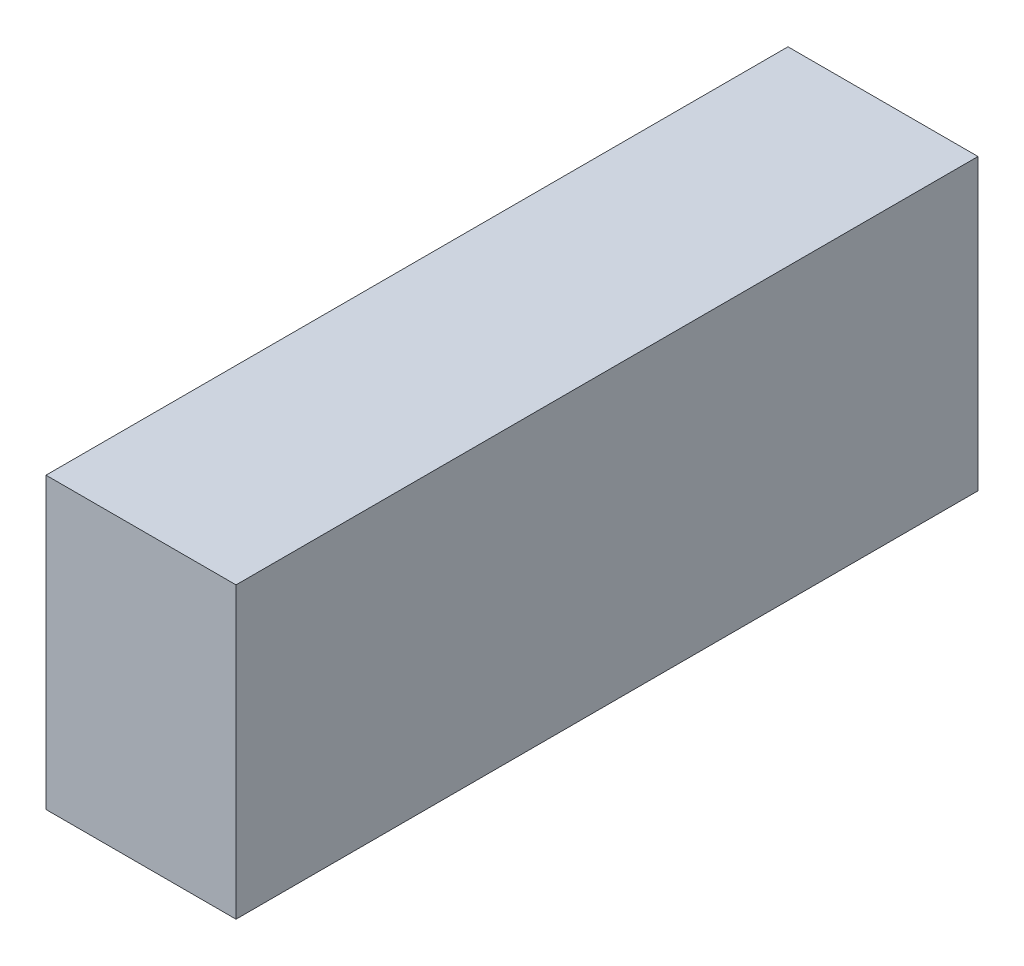
SolidWorks part; units mm, degrees
ref_plane "Front Plane" through (0, 0, 0) normal (0, 0, 1) x (1, 0, 0)
ref_plane "Top Plane" through (0, 0, 0) normal (0, 1, 0) x (1, 0, 0)
ref_plane "Right Plane" through (0, 0, 0) normal (1, 0, 0) x (0, 0, -1)
sketch "Sketch1" plane through (0, 0, 0) normal (0, 0, 1) x (1, 0, 0)
  line L1 (-21, 32) -> (21, 32)
  line L2 (-21, 32) -> (-21, -32)
  line L3 (-21, -32) -> (21, -32)
  line L4 (21, 32) -> (21, -32)
  line L5 (-21, 32) -> (21, -32) construction
  line L6 (-21, -32) -> (21, 32) construction
  point P0 (0, 0)
  dimension "D1" = 42
  dimension "D2" = 64
extrude "Boss-Extrude1" add sketch "Sketch1" along normal blind 164
